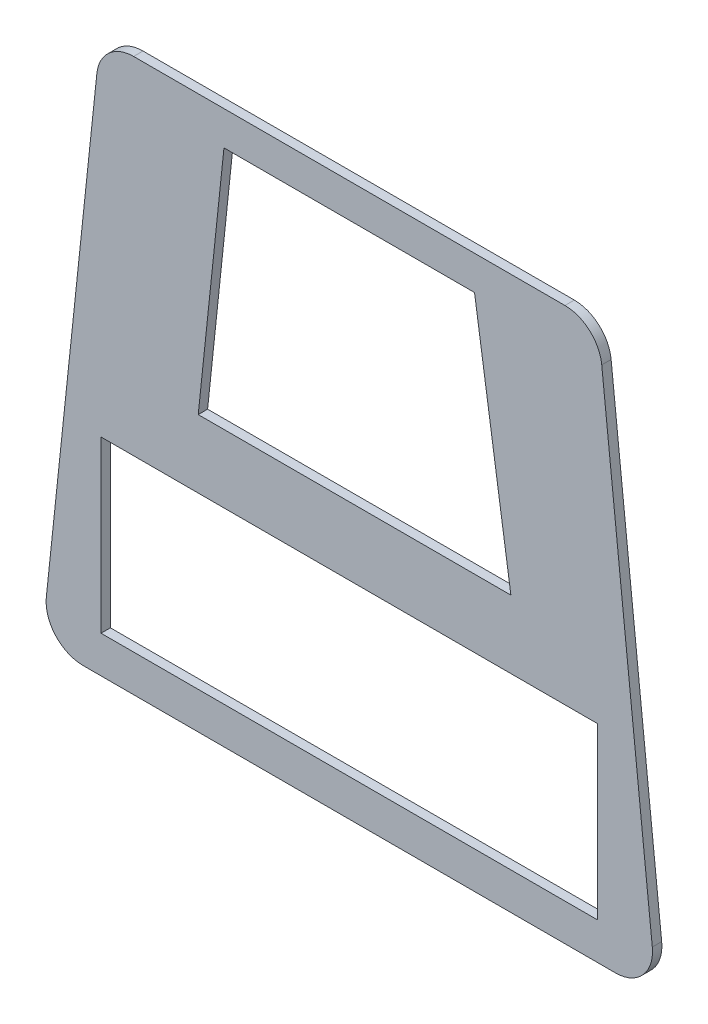
SolidWorks part; units mm, degrees
ref_plane "Front Plane" through (0, 0, 0) normal (0, 0, 1) x (1, 0, 0)
ref_plane "Top Plane" through (0, 0, 0) normal (0, 1, 0) x (1, 0, 0)
ref_plane "Right Plane" through (0, 0, 0) normal (1, 0, 0) x (0, 0, -1)
sketch "Sketch1" plane through (0, 0, 0) normal (0, 0, 1) x (1, 0, 0)
  line L0 (-83, 80.5) -> (83, 80.5)
  line L1 (83, 80.5) -> (107, -80.5)
  line L2 (107, -80.5) -> (-100, -80.5)
  line L3 (-100, -80.5) -> (-83, 80.5)
  line L4 (0, 80.5) -> (0, -80.5) construction
  line L5 (-83, 80.5) -> (-83, -80.5) construction
  line L6 (0, -128.5) -> (0, -243.5) construction
  line L7 (-168, -128.5) -> (168, -128.5)
  line L8 (-168, -128.5) -> (-168, -243.5)
  line L9 (-168, -243.5) -> (168, -243.5)
  line L10 (168, -128.5) -> (168, -243.5)
  line L11 (0, -128.5) -> (0, -80.5) construction
  line L16 (0, 105.5) -> (0, -268.5) construction
  line L17 (83, 80.5) -> (83, -80.5) construction
  line L18 (145.9317, 105.5) -> (-145.9317, 105.5)
  line L19 (-170.7935, 83.1252) -> (-205.0046, -240.8748)
  line L20 (-180.1429, -268.5) -> (180.1429, -268.5)
  line L21 (205.0046, -240.8748) -> (170.7935, 83.1252)
  arc A4 (180.1429, -268.5) -> (205.0046, -240.8748) centre (180.1429, -243.5) ccw
  arc A5 (-205.0046, -240.8748) -> (-180.1429, -268.5) centre (-180.1429, -243.5) ccw
  arc A6 (-145.9317, 105.5) -> (-170.7935, 83.1252) centre (-145.9317, 80.5) ccw
  arc A7 (145.9317, 105.5) -> (170.7935, 83.1252) centre (145.9317, 80.5) cw
  point P6 (0, 0)
  point P17 (0, 0)
  point P20 (0, 105.5)
  point P23 (-147.356, 105.5)
  point P24 (0, 0)
  dimension "D10" = 25
  dimension "D1" = 161
  dimension "D2" = 166
  dimension "D3" = 24
  dimension "D4" = 48
  dimension "D5" = 336
  dimension "D6" = 115
  dimension "D7" = 25
  dimension "D8" = 25
  dimension "D9" = 25
  dimension "D11" = 17
extrude "Boss-Extrude1" add sketch "Sketch1" along normal blind 6.35
sketch "Sketch2" plane through (0, 0, 6.35) normal (0, 0, 1) x (1, 0, 0)
  line L0 (-100, -80.5) -> (107, -80.5) construction
  line L1 (107, -80.5) -> (83, 80.5) construction
  line L2 (83, 80.5) -> (-83, 80.5) construction
  line L3 (-83, 80.5) -> (-100, -80.5) construction
  line L4 (-100, -80.5) -> (107, -80.5) construction
  line L5 (107, -80.5) -> (83, 80.5) construction
  line L6 (83, 80.5) -> (-83, 80.5) construction
  line L7 (-83, 80.5) -> (-100, -80.5) construction
  line L8 (-102.2223, -82.5) -> (109.3202, -82.5)
  line L9 (109.3202, -82.5) -> (84.724, 82.5)
  line L10 (84.724, 82.5) -> (-84.7999, 82.5)
  line L11 (-84.7999, 82.5) -> (-102.2223, -82.5)
  dimension "D1" = 2
extrude "Cut-Extrude1" cut sketch "Sketch2" against normal blind 6.35
